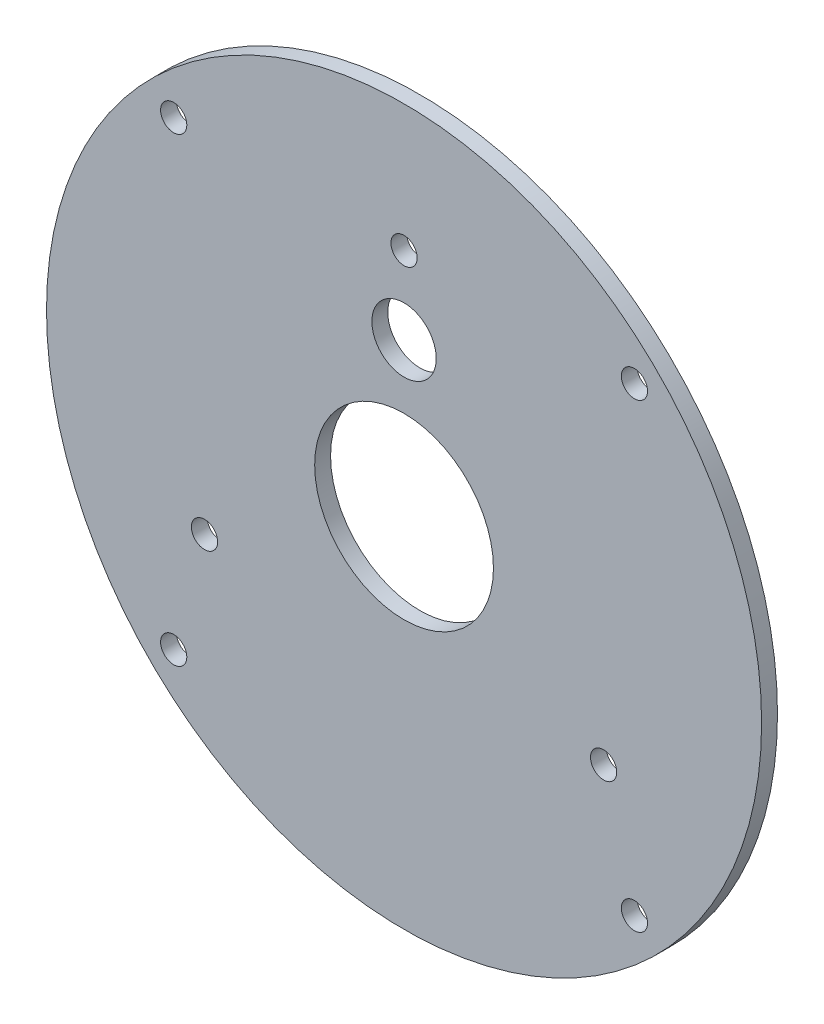
SolidWorks part; units mm, degrees
material "Thornel Mat VMA"
ref_plane "前视基准面" through (0, 0, 0) normal (0, 0, 1) x (1, 0, 0)
ref_plane "上视基准面" through (0, 0, 0) normal (0, 1, 0) x (1, 0, 0)
ref_plane "右视基准面" through (0, 0, 0) normal (1, 0, 0) x (0, 0, -1)
sketch "草图1" plane through (0, 0, 0) normal (0, 0, 1) x (1, 0, 0)
  line L1 (28.9914, -28.9914) -> (-28.9914, -28.9914) construction
  line L2 (28.9914, -28.9914) -> (28.9914, 28.9914) construction
  line L3 (28.9914, 28.9914) -> (-28.9914, 28.9914) construction
  line L4 (-28.9914, -28.9914) -> (-28.9914, 28.9914) construction
  line L5 (28.9914, -28.9914) -> (-28.9914, 28.9914) construction
  line L6 (28.9914, 28.9914) -> (-28.9914, -28.9914) construction
  line L7 (0, 29) -> (-25.1147, -14.5) construction
  line L8 (-25.1147, -14.5) -> (25.1147, -14.5) construction
  line L9 (25.1147, -14.5) -> (0, 29) construction
  circle A0 centre (0, 0) radius 45
  circle A1 centre (-28.9914, 28.9914) radius 1.65
  circle A2 centre (28.9914, 28.9914) radius 1.65
  circle A3 centre (-28.9914, -28.9914) radius 1.65
  circle A4 centre (28.9914, -28.9914) radius 1.65
  circle A5 centre (0, 0) radius 14.5 construction
  circle A6 centre (0, 29) radius 1.65
  circle A7 centre (-25.1147, -14.5) radius 1.65
  circle A8 centre (25.1147, -14.5) radius 1.65
  circle A9 centre (0, 0) radius 10.15
  dimension "D1" = 90
  dimension "D3" = 3.3
  dimension "D4" = 3.3
  dimension "D5" = 3.3
  dimension "D6" = 3.3
  dimension "D8" = 3.3
  dimension "D9" = 3.3
  dimension "D10" = 3.3
  dimension "D11" = 20.3
  dimension "D2" = 41
  dimension "D7" = 29
extrude "凸台-拉伸1" add sketch "草图1" along normal blind 10
sketch "草图2" plane through (0, 0, 10) normal (0, 0, 1) x (1, 0, 0)
  line L1 (0, 19.25) -> (-16.671, -9.625) construction
  line L2 (-16.671, -9.625) -> (16.671, -9.625) construction
  line L3 (16.671, -9.625) -> (0, 19.25) construction
  circle A0 centre (0, 0) radius 9.625 construction
  circle A1 centre (0, 19.25) radius 4.05
  dimension "D1" = 8.1
  dimension "D2" = 19.25
extrude "切除-拉伸1" cut sketch "草图2" against normal blind 12
sketch "草图3" plane through (0, 0, 10) normal (0, 0, 1) x (1, 0, 0)
  line L0 (0, 0) -> (0, 29) construction
  line L1 (0, 0) -> (-25.1147, -14.5) construction
  line L2 (-29, 0) -> (0, 0) construction
  line L3 (0, 0) -> (-14.5, 25.1147) construction
  circle A0 centre (0, 0) radius 29 construction
  arc A1 (-35, 0) -> (-23, 0) centre (-29, 0) ccw
  arc A2 (-11.5, 19.9186) -> (-17.5, 30.3109) centre (-14.5, 25.1147) ccw
  arc A3 (-11.5, 19.9186) -> (-23, 0) centre (0, 0) ccw
  arc A4 (-17.5, 30.3109) -> (-35, 0) centre (0, 0) ccw
  arc A5 (23, 0) -> (35, 0) centre (29, 0) ccw
  arc A6 (35, 0) -> (17.5, 30.3109) centre (0, 0) ccw
  arc A7 (17.5, 30.3109) -> (11.5, 19.9186) centre (14.5, 25.1147) ccw
  arc A8 (23, 0) -> (11.5, 19.9186) centre (0, 0) ccw
  arc A9 (-11.5, -19.9186) -> (-17.5, -30.3109) centre (-14.5, -25.1147) ccw
  arc A10 (-17.5, -30.3109) -> (17.5, -30.3109) centre (0, 0) ccw
  arc A11 (17.5, -30.3109) -> (11.5, -19.9186) centre (14.5, -25.1147) ccw
  arc A12 (-11.5, -19.9186) -> (11.5, -19.9186) centre (0, 0) ccw
  point P27 (0, 0)
  dimension "D1" = 12
  dimension "D2" = 3
  dimension "D3" = 60
  dimension "D4" = 30
extrude "切除-拉伸2" [suppressed] cut sketch "草图3" against normal blind 2
sketch "草图4" plane through (0, 0, 10) normal (0, 0, 1) x (1, 0, 0)
  circle A0 centre (18.7661, 11.482) radius 7.5
  dimension "D1" = 15
  dimension "D2" = 22
extrude "切除-拉伸3" [suppressed] cut sketch "草图4" against normal blind 2
fillet "圆角1" [suppressed] radius 10
sketch "草图5" plane through (0, 0, 0) normal (0, 0, -1) x (-1, 0, 0)
  circle A0 centre (0, 0) radius 34.5
  dimension "D1" = 69
extrude "切除-拉伸4" cut sketch "草图5" against normal blind 3
sketch "草图7" plane through (0, 0, 3) normal (0, 0, -1) x (-1, 0, 0)
  line L0 (0, 0) -> (80.8357, 0) construction
  line L1 (0, 0) -> (28.9914, -28.9914) construction
  line L2 (0, 0) -> (-25.0711, -53.7652)
  line L3 (-25.0711, -53.7652) -> (25.216, -54.0758)
  line L4 (25.216, -54.0758) -> (0, 0)
  line L5 (-28.9914, -28.9914) -> (0, 0) construction
  dimension "D1" = 20
  dimension "D2" = 20
extrude "切除-拉伸6" cut sketch "草图7" along normal up to surface (3 mm away) contours L4 L2 L3 up to face at (-34.5, 0, 0)
sketch "草图10" plane through (0, 0, 0) normal (0, 0, -1) x (-1, 0, 0)
  circle A0 centre (0, 0) radius 45
extrude "切除-拉伸9" cut sketch "草图10" against normal blind 8
sketch "草图11" plane through (0, 0, 8) normal (0, 0, -1) x (-1, 0, 0)
  circle A0 centre (0, 0) radius 11.25
  dimension "D1" = 22.5
extrude "切除-拉伸10" cut sketch "草图11" against normal blind 10
